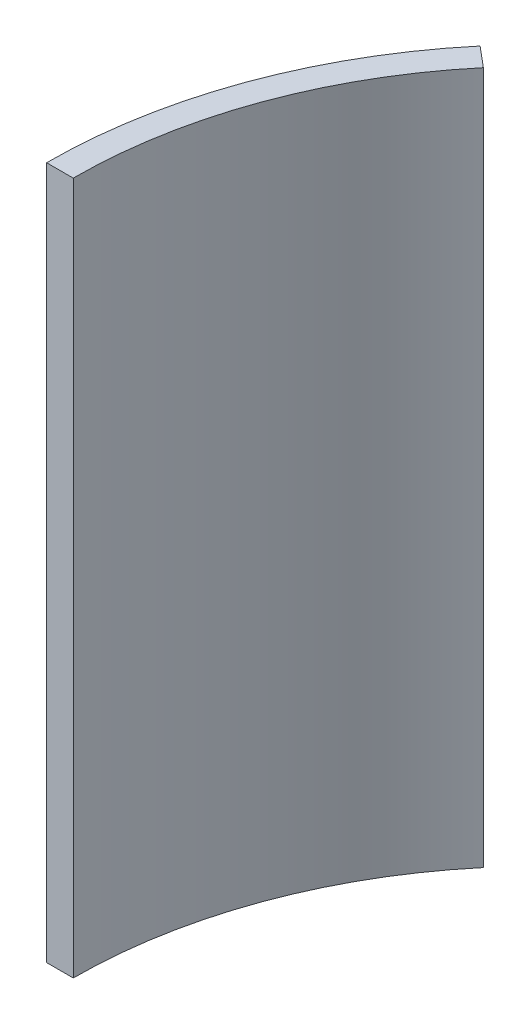
SolidWorks part; units mm, degrees
material "Custom Plastic"
ref_plane "Front Plane" through (0, 0, 0) normal (0, 0, 1) x (1, 0, 0)
ref_plane "Top Plane" through (0, 0, 0) normal (0, 1, 0) x (1, 0, 0)
ref_plane "Right Plane" through (0, 0, 0) normal (1, 0, 0) x (0, 0, -1)
sketch "Sketch1" plane through (0, 0, 0) normal (0, 1, 0) x (1, 0, 0)
  line L0 (0, 0) -> (65.2704, 0) construction
  line L1 (65.2704, 0) -> (65.2704, 50) construction
  line L2 (0, 0) -> (0, -10) construction
  line L3 (18.1985, 50) -> (-23.7565, 0) construction
  line L4 (10, 0) -> (-10, 0)
  line L5 (25.859, 43.5721) -> (10.5381, 56.4279)
  arc A0 (0, 0) -> (18.1985, 50) centre (77.7862, 0) cw construction
  arc A1 (10, 0) -> (25.859, 43.5721) centre (77.7862, 0) cw
  arc A2 (-10, 0) -> (10.5381, 56.4279) centre (77.7862, 0) cw
  circle A3 centre (0.6455, 10) radius 2.6
  circle A4 centre (4.6911, 26.6044) radius 2.6
  circle A5 centre (12.2651, 41.9247) radius 2.6
  circle A7 centre (23.0019, 55.2211) radius 2.6 [skipped]
  point P24 (77.7862, 0)
  dimension "D6" = 5.2
  dimension "D9" = 10
  dimension "D1" = 10
  dimension "D2" = 50
  dimension "D3" = 50
  dimension "D7" = 10
  dimension "D8" = 4
  dimension "D4" = 10
  dimension "D5" = 10
extrude "Boss-Extrude1" add sketch "Sketch1" along normal blind 20
sketch "Sketch2" plane through (0, 20, 0) normal (0, 1, 0) x (1, 0, 0)
  line L0 (6.7078, 59.6418) -> (10.5381, 56.4279)
  line L1 (-15, 0) -> (-10, 0)
  arc A1 (10.5381, 56.4279) -> (-10, 0) centre (77.7862, 0) ccw construction
  arc A2 (6.7078, 59.6418) -> (-15, 0) centre (77.7862, 0) ccw
  arc A3 (6.7078, 59.6418) -> (-15, 0) centre (77.7862, 0) ccw
  arc A4 (10.5381, 56.4279) -> (-10, 0) centre (77.7862, 0) ccw
  dimension "D1" = 5
extrude "Boss-Extrude2" add sketch "Sketch2" along normal blind 130 separate body
sketch "Sketch3" plane through (0, 20, 0) normal (0, 1, 0) x (1, 0, 0)
  line L2 (25.859, 43.5721) -> (10.5381, 56.4279)
  line L3 (-10, 0) -> (10, 0)
  line L4 (25.859, 43.5721) -> (10.5381, 56.4279)
  line L5 (-10, 0) -> (10, 0)
  arc A2 (25.859, 43.5721) -> (10, 0) centre (77.7862, 0) ccw
  arc A3 (10.5381, 56.4279) -> (-10, 0) centre (77.7862, 0) ccw
  arc A4 (25.859, 43.5721) -> (10, 0) centre (77.7862, 0) ccw
  arc A5 (10.5381, 56.4279) -> (-10, 0) centre (77.7862, 0) ccw
  dimension "D1" = 0
extrude "Cut-Extrude1" cut sketch "Sketch3" against normal through all
